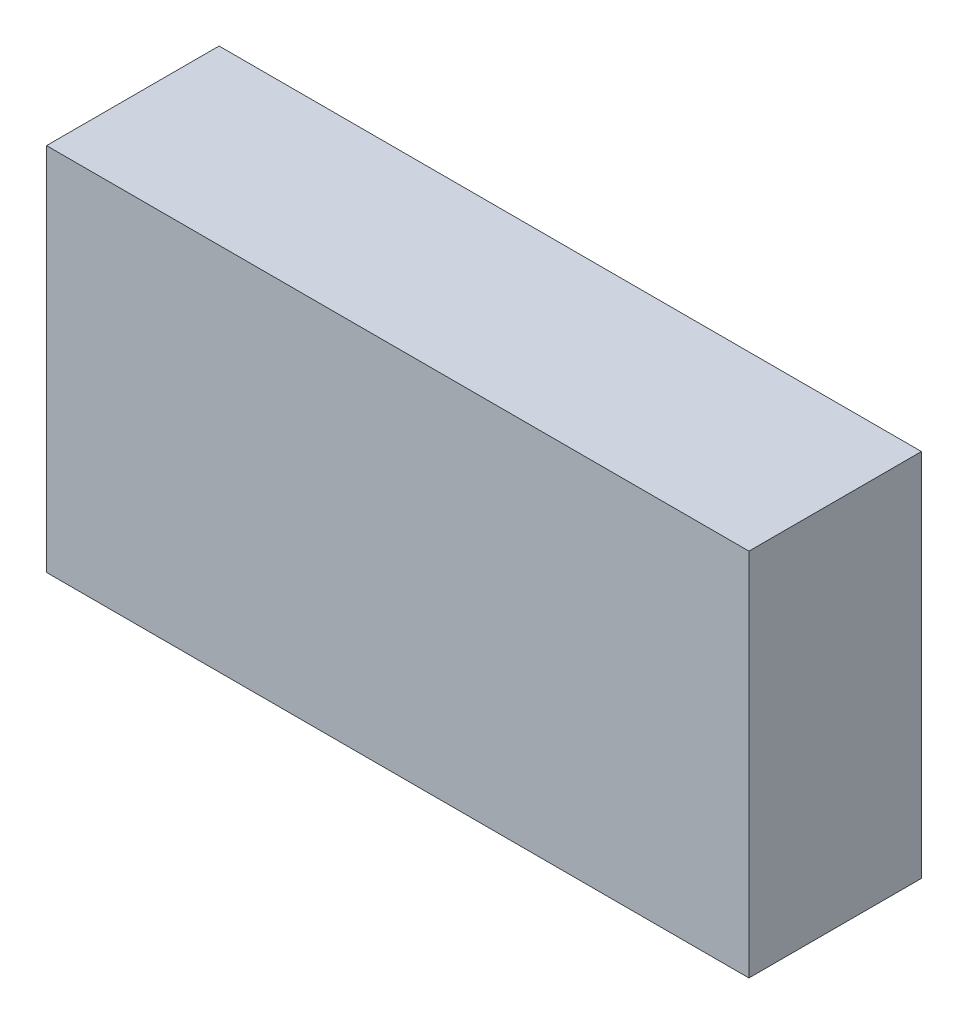
SolidWorks part; units mm, degrees
ref_plane "Front Plane" through (0, 0, 0) normal (0, 0, 1) x (1, 0, 0)
ref_plane "Top Plane" through (0, 0, 0) normal (0, 1, 0) x (1, 0, 0)
ref_plane "Right Plane" through (0, 0, 0) normal (1, 0, 0) x (0, 0, -1)
sketch "Sketch1" plane through (0, 0, 0) normal (0, 0, 1) x (1, 0, 0)
  line L1 (28.5, -15) -> (-28.5, -15)
  line L2 (28.5, -15) -> (28.5, 15)
  line L3 (28.5, 15) -> (-28.5, 15)
  line L4 (-28.5, -15) -> (-28.5, 15)
  line L5 (28.5, -15) -> (-28.5, 15) construction
  line L6 (28.5, 15) -> (-28.5, -15) construction
  point P0 (0, 0)
  dimension "D1" = 57
  dimension "D2" = 30
extrude "Boss-Extrude1" add sketch "Sketch1" along normal blind 14
